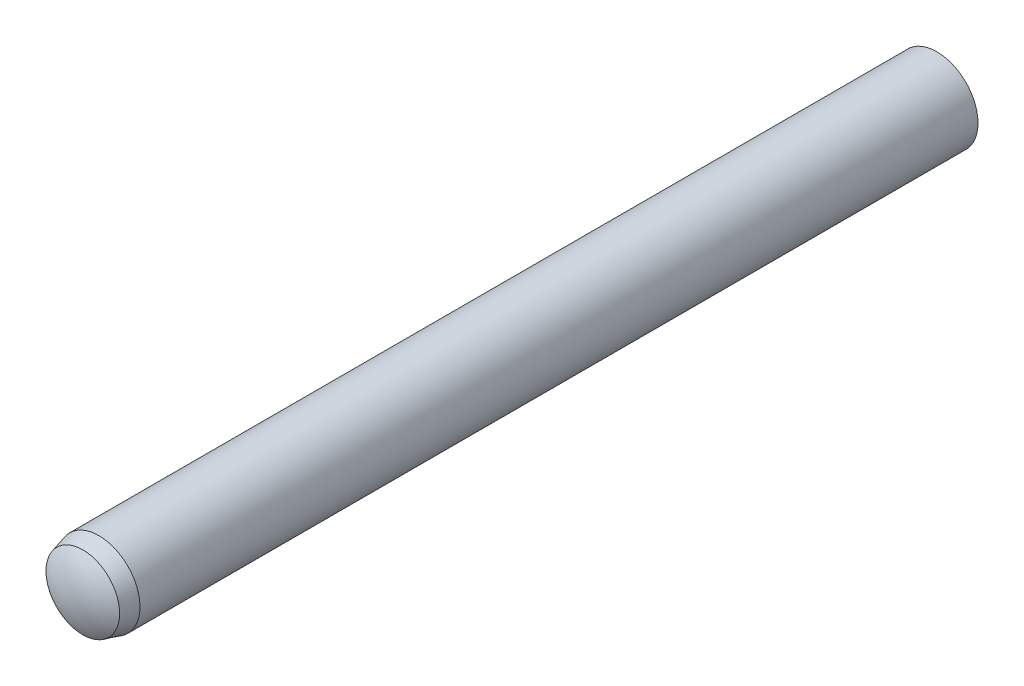
SolidWorks part; units mm, degrees
ref_plane "Front Plane" through (0, 0, 0) normal (0, 0, 1) x (1, 0, 0)
ref_plane "Top Plane" through (0, 0, 0) normal (0, 1, 0) x (1, 0, 0)
ref_plane "Right Plane" through (0, 0, 0) normal (1, 0, 0) x (0, 0, -1)
sketch "Sketch1" plane through (0, 0, 0) normal (0, 0, 1) x (1, 0, 0)
  circle A0 centre (0, 0) radius 1.5
  point P3 (0, 1.5)
  dimension "Diameter" = 3
sketch "Sketch2" plane through (0, 0, 0) normal (1, 0, 0) x (0, 0, -1)
  line L0 (-16, 0) -> (16, 0) construction
  line L1 (-16, 0) -> (-16, 1.5) construction
  line L2 (-16, 1.5) -> (16, 1.5)
  line L3 (16, 1.5) -> (16, 0) construction
  line L4 (-15.61, 1.3432) -> (-15.025, 1.5)
  arc A0 (-16, 0) -> (-15.61, 1.3432) centre (-13.4918, 0) cw
  arc A1 (16, 0) -> (15.55, 1.5) centre (13.275, 0) ccw
  point P2 (0, 0)
  point P11 (-13, 0)
  point P13 (13, 0)
  dimension "Length" = 32
  dimension "D1" = 15
  dimension "D2" = 0.45
  dimension "D3" = 0.975
  dimension "D4" = 0.585
  dimension "D5" = 3
  dimension "D6" = 3
sketch "Sketch3" plane through (0, 0, 0) normal (1, 0, 0) x (0, 0, -1)
  line L0 (-16, 0) -> (16, 0) construction
  line L1 (-15.61, 1.3432) -> (-15.025, 1.5) construction
  line L2 (-16, 0) -> (16, 0)
  line L3 (-15.61, 1.3432) -> (-15.025, 1.5)
  line L4 (-15.025, 1.5) -> (15.55, 1.5)
  arc A0 (16, 0) -> (15.55, 1.5) centre (13.275, 0) ccw construction
  arc A1 (-15.61, 1.3432) -> (-16, 0) centre (-13.4918, 0) ccw construction
  arc A2 (16, 0) -> (15.55, 1.5) centre (13.275, 0) ccw
  arc A3 (-15.61, 1.3432) -> (-16, 0) centre (-13.4918, 0) ccw
revolve "Revolve1" add sketch "Sketch3" angle 360 about L2
equation "\"D2@Sketch2\" = \"Diameter@Sketch1\" * .15"
equation "\"D3@Sketch2\" = \"Diameter@Sketch1\" * .325"
equation "\"D4@Sketch2\" = \"D3@Sketch2\" * .6"
equation "\"D5@Sketch2\"=\"Diameter@Sketch1\""
equation "\"D6@Sketch2\"=\"D5@sketch2\""
